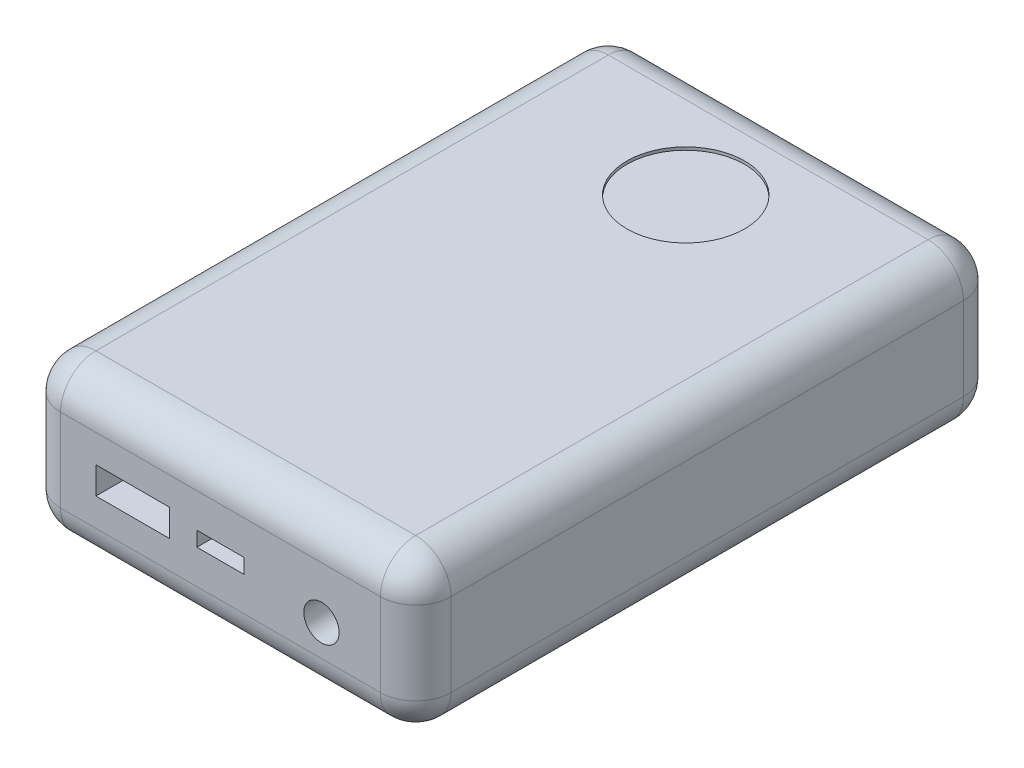
SolidWorks part; units mm, degrees
material "ABS"
ref_plane "Front Plane" through (0, 0, 0) normal (0, 0, 1) x (1, 0, 0)
ref_plane "Top Plane" through (0, 0, 0) normal (0, 1, 0) x (1, 0, 0)
ref_plane "Right Plane" through (0, 0, 0) normal (1, 0, 0) x (0, 0, -1)
sketch "Sketch1" plane through (0, 0, 0) normal (0, 0, 1) x (1, 0, 0)
  line L0 (0, 0) -> (0, 82.5412) construction
  line L1 (-33.15, 0) -> (33.15, 0)
  line L2 (-33.15, 0) -> (-33.15, 26.1)
  line L3 (-33.15, 26.1) -> (33.15, 26.1)
  line L4 (33.15, 0) -> (33.15, 26.1)
  dimension "D1" = 26.1
  dimension "D2" = 66.3
extrude "Boss-Extrude1" add sketch "Sketch1" along normal mid plane 99
sketch "Sketch2" plane through (0, 0, 49.5) normal (0, 0, 1) x (1, 0, 0)
  line L0 (0, 0) -> (0, 26.1) construction
  line L1 (33.15, 26.1) -> (-33.15, 26.1) construction
  line L2 (0, 13.05) -> (-33.15, 13.05) construction
  line L3 (-33.15, 26.1) -> (-33.15, 0) construction
  line L4 (33.15, 0) -> (33.15, 26.1) construction
  line L5 (-21.15, 15.35) -> (-8.65, 15.35)
  line L6 (-21.15, 15.35) -> (-21.15, 10.75)
  line L7 (-21.15, 10.75) -> (-8.65, 10.75)
  line L8 (-8.65, 15.35) -> (-8.65, 10.75)
  line L9 (-21.15, 15.35) -> (-8.65, 10.75) construction
  line L10 (-21.15, 10.75) -> (-8.65, 15.35) construction
  line L11 (-4, 14.3) -> (4, 14.3)
  line L12 (-4, 14.3) -> (-4, 11.8)
  line L13 (-4, 11.8) -> (4, 11.8)
  line L14 (4, 14.3) -> (4, 11.8)
  line L15 (-4, 14.3) -> (4, 11.8) construction
  line L16 (-4, 11.8) -> (4, 14.3) construction
  line L17 (4, 14.3) -> (17.15, 14.3) construction
  circle A1 centre (17.15, 11.3) radius 3
  point P10 (-14.9, 13.05)
  dimension "D6" = 6
  dimension "D7" = 16
  dimension "D1" = 12.5
  dimension "D2" = 4.6
  dimension "D3" = 12
  dimension "D4" = 8
  dimension "D5" = 2.5
extrude "connectors" cut sketch "Sketch2" against normal blind 13
sketch "Sketch4" plane through (0, 26.1, 0) normal (0, 1, 0) x (1, 0, 0)
  line L0 (33.15, 49.5) -> (-33.15, 49.5) construction
  circle A0 centre (0, 29.5) radius 10
  dimension "D2" = 20
  dimension "D1" = 20
extrude "display" cut sketch "Sketch4" against normal blind 0.5 contours A0
fillet "Fillet1" radius 6 12 edges at (33.15, 26.1, 0) (0, 26.1, 49.5) (-33.15, 26.1, 0) (0, 26.1, -49.5) (0, 0, -49.5) (-33.15, 0, 0) (0, 0, 49.5) (33.15, 0, 0) (-33.15, 13.05, -49.5) (-33.15, 13.05, 49.5) (33.15, 13.05, 49.5) (33.15, 13.05, -49.5)
